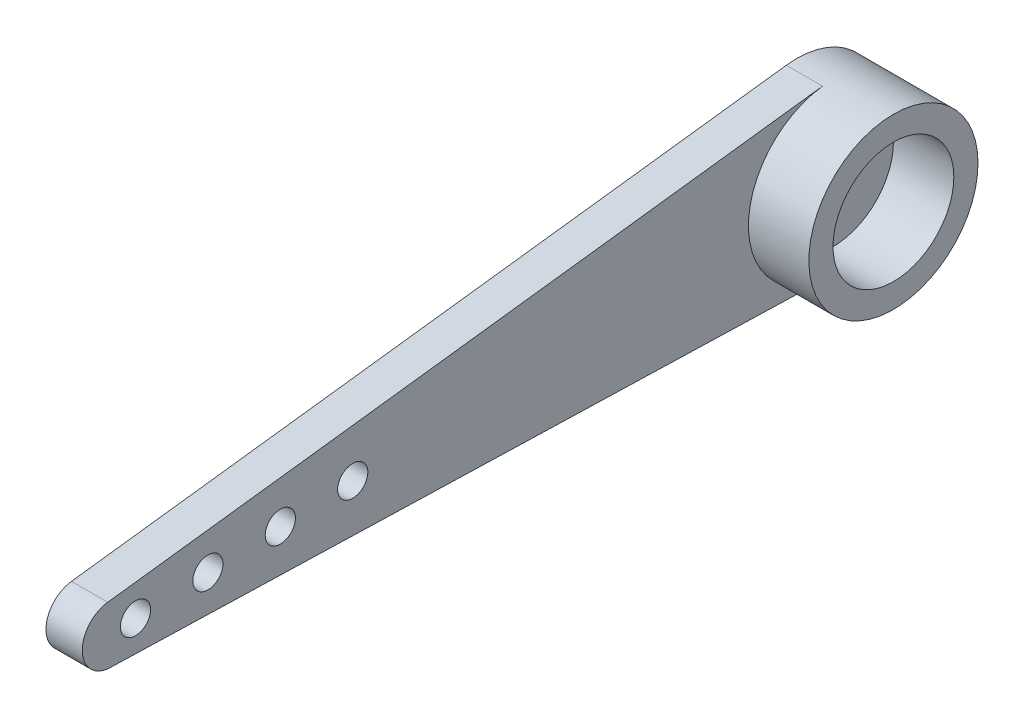
SolidWorks part; units mm, degrees
ref_plane "Front Plane" through (0, 0, 0) normal (0, 0, 1) x (1, 0, 0)
ref_plane "Top Plane" through (0, 0, 0) normal (0, 1, 0) x (1, 0, 0)
ref_plane "Right Plane" through (0, 0, 0) normal (1, 0, 0) x (0, 0, -1)
sketch "Base Sketch" plane through (-4, 0, 0) normal (-1, 0, 0) x (0, 0, 1)
  line L6 (-71.3999, 12.1778) -> (-41.8201, 8.4717)
  line L7 (-71.7326, 5.2065) -> (-41.821, 6.0817)
  line L8 (-71.835, 8.705) -> (-41.9698, 7.2768) construction
  circle A4 centre (-45.9653, 7.4678) radius 0.625
  circle A5 centre (-48.9618, 7.6111) radius 0.625
  circle A6 centre (-51.9584, 7.7544) radius 0.625
  arc A17 (-71.3999, 12.1778) -> (-71.7326, 5.2065) centre (-71.835, 8.705) ccw
  arc A18 (-41.8201, 8.4717) -> (-41.821, 6.0817) centre (-41.9698, 7.2768) cw
  circle A21 centre (-42.9687, 7.3245) radius 0.625
  dimension "D1" = 1.25
  dimension "D2" = 1
  dimension "D3" = 4
extrude "Base Extrude" add sketch "Base Sketch" against normal up to surface (1.5 mm away)
sketch "Circle Sketch" plane through (-2.5, 0, 0) normal (1, 0, 0) x (0, 0, -1)
  circle A0 centre (71.835, 8.705) radius 3.5
  circle A2 centre (71.835, 8.705) radius 2.5
  dimension "D1" = 5
extrude "Circle Extrude" add sketch "Circle Sketch" along normal up to surface (2.5 mm away)
sketch "Screw Circle1 Sketch" plane through (-4, 0, 0) normal (-1, 0, 0) x (0, 0, 1)
  circle A0 centre (-71.835, 8.705) radius 2.5 construction
  circle A1 centre (-71.835, 8.705) radius 2.5
extrude "Screw Circle 1 Cut" cut sketch "Screw Circle1 Sketch" against normal blind 0.6
sketch "Screw Circle2 Sketch" plane through (-4, 0, 0) normal (-1, 0, 0) x (0, 0, 1)
  circle A0 centre (-71.835, 8.705) radius 1 construction
  circle A1 centre (-71.835, 8.705) radius 1
extrude "Screw Circle Cut" cut sketch "Screw Circle2 Sketch" against normal through all
